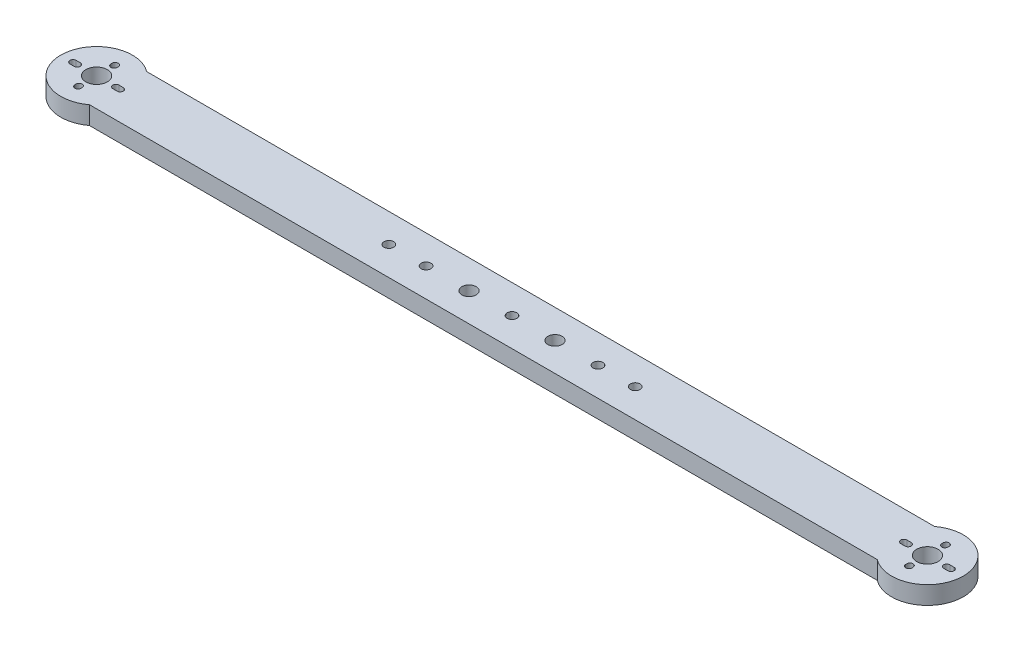
SolidWorks part; units mm, degrees
material "Thornel Mat VMA"
ref_plane "Front Plane" through (0, 0, 0) normal (0, 0, 1) x (1, 0, 0)
ref_plane "Top Plane" through (0, 0, 0) normal (0, 1, 0) x (1, 0, 0)
ref_plane "Right Plane" through (0, 0, 0) normal (1, 0, 0) x (0, 0, -1)
sketch "Sketch1" plane through (0, 0, 0) normal (0, 1, 0) x (1, 0, 0)
  line L0 (0, 12.7) -> (0, -12.7) construction
  line L1 (-174.625, 12.7) -> (174.625, 12.7)
  line L3 (-174.625, -12.7) -> (174.625, -12.7)
  arc A0 (-174.625, 12.7) -> (-174.625, -12.7) centre (-184.15, 0) ccw
  arc A1 (174.625, -12.7) -> (174.625, 12.7) centre (184.15, 0) ccw
  point P8 (0, 12.7)
  point P12 (0, 0)
  dimension "D3" = 31.75
  dimension "D4" = 31.75
extrude "Boss-Extrude1" add sketch "Sketch1" along normal blind 8
sketch "Sketch2" plane through (0, 8, 0) normal (0, 1, 0) x (1, 0, 0)
  line L0 (173.6914, 0) -> (175.6086, 0) construction
  line L1 (173.6914, 1.375) -> (175.6086, 1.375)
  line L2 (173.6914, -1.375) -> (175.6086, -1.375)
  line L3 (184.15, 0) -> (184.15, 3.2374) construction
  line L4 (194.6086, 0) -> (192.6914, 0) construction
  line L5 (194.6086, 1.375) -> (192.6914, 1.375)
  line L6 (194.6086, -1.375) -> (192.6914, -1.375)
  line L7 (184.15, 8.25) -> (184.15, 7.75) construction
  line L8 (185.525, 8.25) -> (185.525, 7.75)
  line L9 (182.775, 8.25) -> (182.775, 7.75)
  line L10 (184.15, -8.25) -> (184.15, -7.75) construction
  line L11 (185.525, -8.25) -> (185.525, -7.75)
  line L12 (182.775, -8.25) -> (182.775, -7.75)
  line L13 (0, 0) -> (184.15, 0) construction
  line L14 (0, 0) -> (0, 12.7) construction
  line L15 (174.625, 12.7) -> (-174.625, 12.7) construction
  line L16 (-184.15, 0) -> (-184.15, 3.2374) construction
  line L17 (-184.15, -8.25) -> (-184.15, -7.75) construction
  line L18 (-185.525, -8.25) -> (-185.525, -7.75)
  line L19 (-182.775, -8.25) -> (-182.775, -7.75)
  line L20 (-184.15, 8.25) -> (-184.15, 7.75) construction
  line L21 (-185.525, 8.25) -> (-185.525, 7.75)
  line L22 (-182.775, 8.25) -> (-182.775, 7.75)
  line L23 (-194.6086, 0) -> (-192.6914, 0) construction
  line L24 (-194.6086, 1.375) -> (-192.6914, 1.375)
  line L25 (-194.6086, -1.375) -> (-192.6914, -1.375)
  line L26 (-173.6914, 0) -> (-175.6086, 0) construction
  line L27 (-173.6914, 1.375) -> (-175.6086, 1.375)
  line L28 (-173.6914, -1.375) -> (-175.6086, -1.375)
  line L29 (184.15, 8) -> (184.15, -8) construction
  circle A0 centre (184.15, 0) radius 4.75
  arc A1 (173.6914, 1.375) -> (173.6914, -1.375) centre (173.6914, 0) ccw
  arc A2 (175.6086, -1.375) -> (175.6086, 1.375) centre (175.6086, 0) ccw
  arc A3 (194.6086, 1.375) -> (194.6086, -1.375) centre (194.6086, 0) cw
  arc A4 (192.6914, -1.375) -> (192.6914, 1.375) centre (192.6914, 0) cw
  arc A5 (185.525, 8.25) -> (182.775, 8.25) centre (184.15, 8.25) ccw
  arc A6 (182.775, 7.75) -> (185.525, 7.75) centre (184.15, 7.75) ccw
  arc A7 (185.525, -8.25) -> (182.775, -8.25) centre (184.15, -8.25) cw
  arc A8 (182.775, -7.75) -> (185.525, -7.75) centre (184.15, -7.75) cw
  circle A9 centre (-184.15, 0) radius 4.75
  arc A10 (-185.525, -8.25) -> (-182.775, -8.25) centre (-184.15, -8.25) ccw
  arc A11 (-182.775, -7.75) -> (-185.525, -7.75) centre (-184.15, -7.75) ccw
  arc A12 (-185.525, 8.25) -> (-182.775, 8.25) centre (-184.15, 8.25) cw
  arc A13 (-182.775, 7.75) -> (-185.525, 7.75) centre (-184.15, 7.75) cw
  arc A14 (-194.6086, 1.375) -> (-194.6086, -1.375) centre (-194.6086, 0) ccw
  arc A15 (-192.6914, -1.375) -> (-192.6914, 1.375) centre (-192.6914, 0) ccw
  arc A16 (-173.6914, 1.375) -> (-173.6914, -1.375) centre (-173.6914, 0) cw
  arc A17 (-175.6086, -1.375) -> (-175.6086, 1.375) centre (-175.6086, 0) cw
  point P4 (174.65, 0)
  point P12 (193.65, 0)
  point P19 (184.15, 8)
  point P26 (184.15, -8)
  point P41 (-184.15, -8)
  point P48 (-184.15, 8)
  point P55 (-193.65, 0)
  point P62 (-174.65, 0)
  point P67 (184.15, 0)
  dimension "D4" = 9.5
  dimension "D1" = 16
  dimension "D2" = 19
  dimension "D3" = 184.15
  dimension "D5" = 0.5
  dimension "D6" = 0.5
extrude "Cut-Extrude1" cut sketch "Sketch2" against normal through all
sketch "Sketch3" plane through (0, 8, 0) normal (0, 1, 0) x (1, 0, 0)
  circle A0 centre (0, 0) radius 2.159
  circle A1 centre (38.1, 0) radius 2.159
  circle A2 centre (-38.1, 0) radius 2.159
  dimension "D1" = 38.1
  dimension "D3" = 4.318
  dimension "D4" = 4.318
  dimension "D5" = 4.318
  dimension "D2" = 38.1
extrude "Cut-Extrude2" cut sketch "Sketch3" against normal through all
sketch "Sketch4" plane through (0, 8, 0) normal (0, 1, 0) x (1, 0, 0)
  circle A0 centre (-19.05, 0) radius 3.175
  circle A1 centre (19.05, 0) radius 3.175
  dimension "D1" = 19.05
  dimension "D2" = 19.05
extrude "Cut-Extrude3" cut sketch "Sketch4" against normal through all
sketch "Sketch5" plane through (0, 8, 0) normal (0, 1, 0) x (1, 0, 0)
  line L0 (0, 12.7) -> (0, -22.99) construction
  line L1 (174.625, 12.7) -> (-174.625, 12.7) construction
  circle A0 centre (54.61, 0) radius 2.159
  circle A1 centre (184.15, 0) radius 4.75 construction
  circle A2 centre (-54.61, 0) radius 2.159
  dimension "D1" = 4.318
  dimension "D2" = 129.54
extrude "Cut-Extrude4" cut sketch "Sketch5" against normal through all
